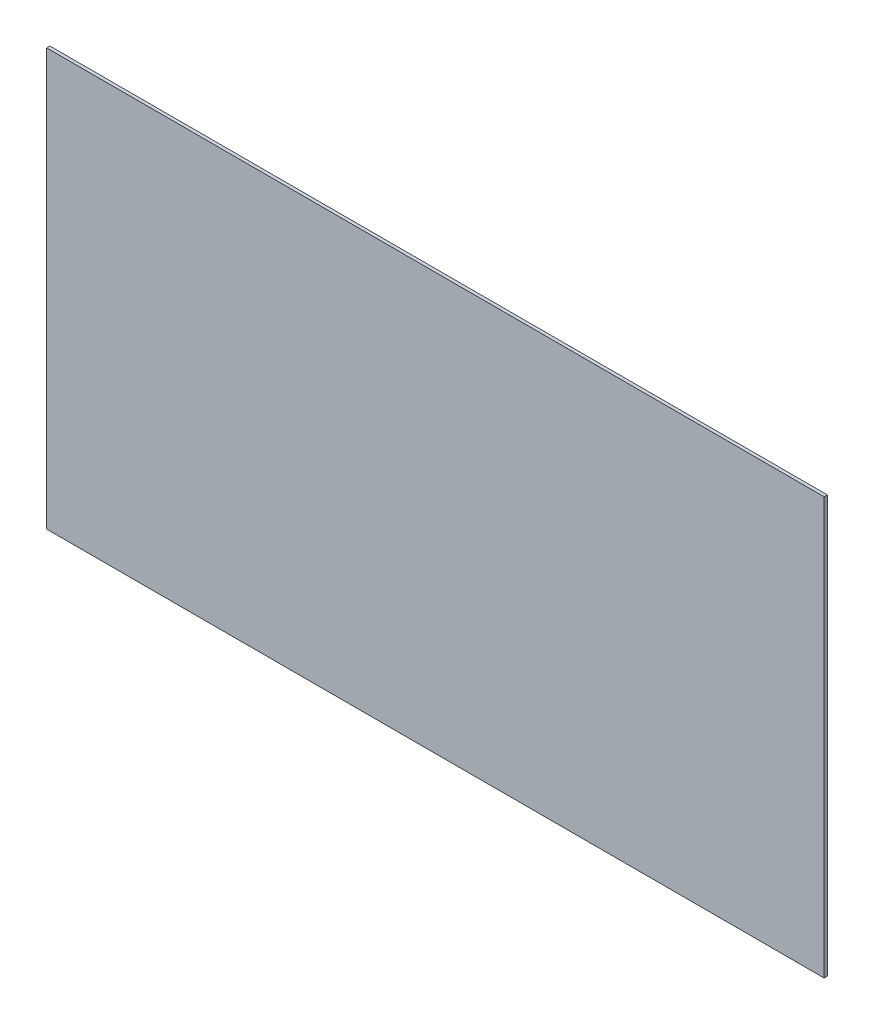
SolidWorks part; units mm, degrees
material "Glas"
ref_plane "Ebene vorne" through (0, 0, 0) normal (0, 0, 1) x (1, 0, 0)
ref_plane "Ebene oben" through (0, 0, 0) normal (0, 1, 0) x (1, 0, 0)
ref_plane "Ebene rechts" through (0, 0, 0) normal (1, 0, 0) x (0, 0, -1)
sketch "Skizze1" plane through (0, 0, 0) normal (0, 0, 1) x (1, 0, 0)
  line L1 (0, 0) -> (485, 0)
  line L2 (0, 0) -> (0, 260)
  line L3 (0, 260) -> (485, 260)
  line L4 (485, 0) -> (485, 260)
  dimension "D1" = 485
  dimension "D2" = 260
extrude "Aufsatz-Linear austragen1" add sketch "Skizze1" along normal blind 2
